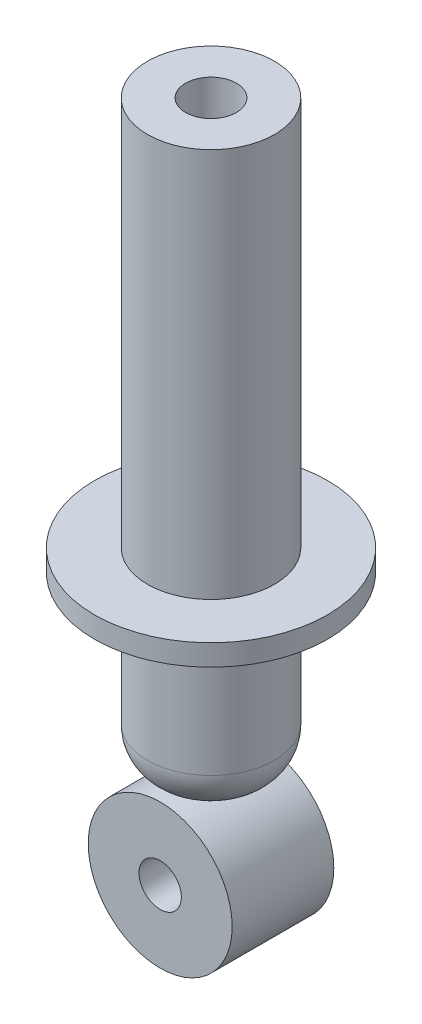
SolidWorks part; units mm, degrees
ref_plane "Спереди" through (0, 0, 0) normal (0, 0, 1) x (1, 0, 0)
ref_plane "Сверху" through (0, 0, 0) normal (0, 1, 0) x (1, 0, 0)
ref_plane "Справа" through (0, 0, 0) normal (1, 0, 0) x (0, 0, -1)
sketch "Эскиз1" plane through (0, 0, 0) normal (0, 1, 0) x (1, 0, 0)
  circle A0 centre (0, 0) radius 15
  dimension "D1" = 30
extrude "Бобышка-Вытянуть1" add sketch "Эскиз1" along normal blind 136
sketch "Эскиз2" plane through (0, 136, 0) normal (0, 1, 0) x (1, 0, 0)
  circle A0 centre (0, 0) radius 15
  circle A1 centre (0, 0) radius 6
  dimension "D1" = 12
extrude "Бобышка-Вытянуть2" add sketch "Эскиз2" along normal blind 2
sketch "Эскиз3" plane through (0, 136, 0) normal (0, 1, 0) x (1, 0, 0)
  circle A0 centre (0, 0) radius 6
extrude "Вырез-Вытянуть1" cut sketch "Эскиз3" against normal blind 130
sketch "Эскиз4" plane through (0, 0, 0) normal (0, 0, 1) x (1, 0, 0)
  circle A0 centre (0, -17) radius 17
  circle A1 centre (0, -17) radius 5
  dimension "D1" = 34
  dimension "D3" = 10
  dimension "D2" = 17
extrude "Бобышка-Вытянуть3" add sketch "Эскиз4" along normal mid plane 24 separate body
fillet "Скругление1" radius 10 1 edges at (0, 0, 15)
ref_plane "Плоскость1" through (0, 41, 0) normal (0, 1, 0) x (1, 0, 0)
sketch "Эскиз6" plane through (0, 41, 0) normal (0, 1, 0) x (1, 0, 0)
  circle A0 centre (0, 0) radius 27.5
  circle A1 centre (0, 0) radius 15
  dimension "D1" = 55
extrude "Бобышка-Вытянуть4" add sketch "Эскиз6" along normal blind 5
